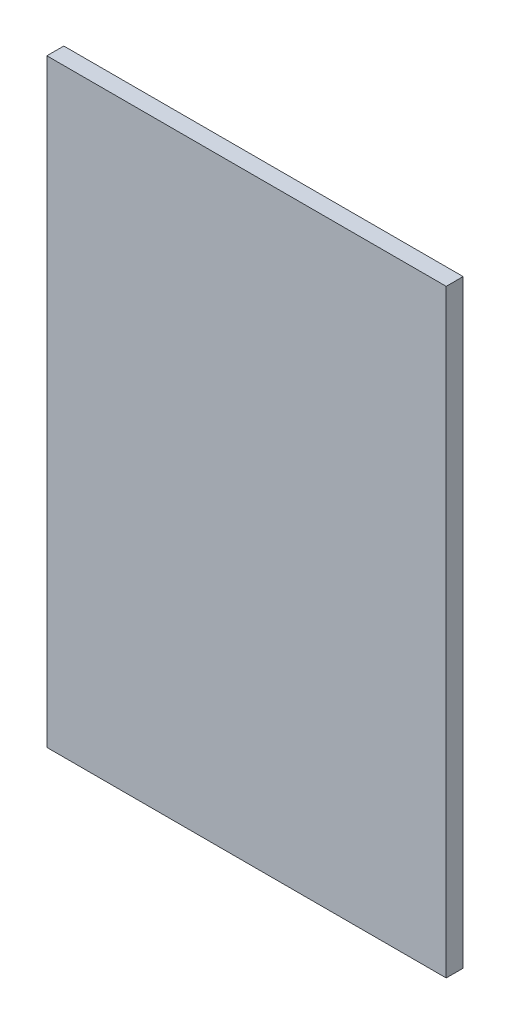
SolidWorks part; units mm, degrees
ref_plane "Front Plane" through (0, 0, 0) normal (0, 0, 1) x (1, 0, 0)
ref_plane "Top Plane" through (0, 0, 0) normal (0, 1, 0) x (1, 0, 0)
ref_plane "Right Plane" through (0, 0, 0) normal (1, 0, 0) x (0, 0, -1)
sketch "Sketch1" plane through (0, 0, 0) normal (0, 1, 0) x (1, 0, 0)
  line L1 (-374.65, 12.7) -> (224.79, 12.7)
  line L2 (-374.65, 12.7) -> (-374.65, -12.7)
  line L3 (-374.65, -12.7) -> (224.79, -12.7)
  line L4 (224.79, 12.7) -> (224.79, -12.7)
  dimension "D1" = 599.44
  dimension "D2" = 25.4
  dimension "D3" = 374.65
  dimension "D4" = 12.7
extrude "Boss-Extrude1" add sketch "Sketch1" along normal mid plane 899.16
